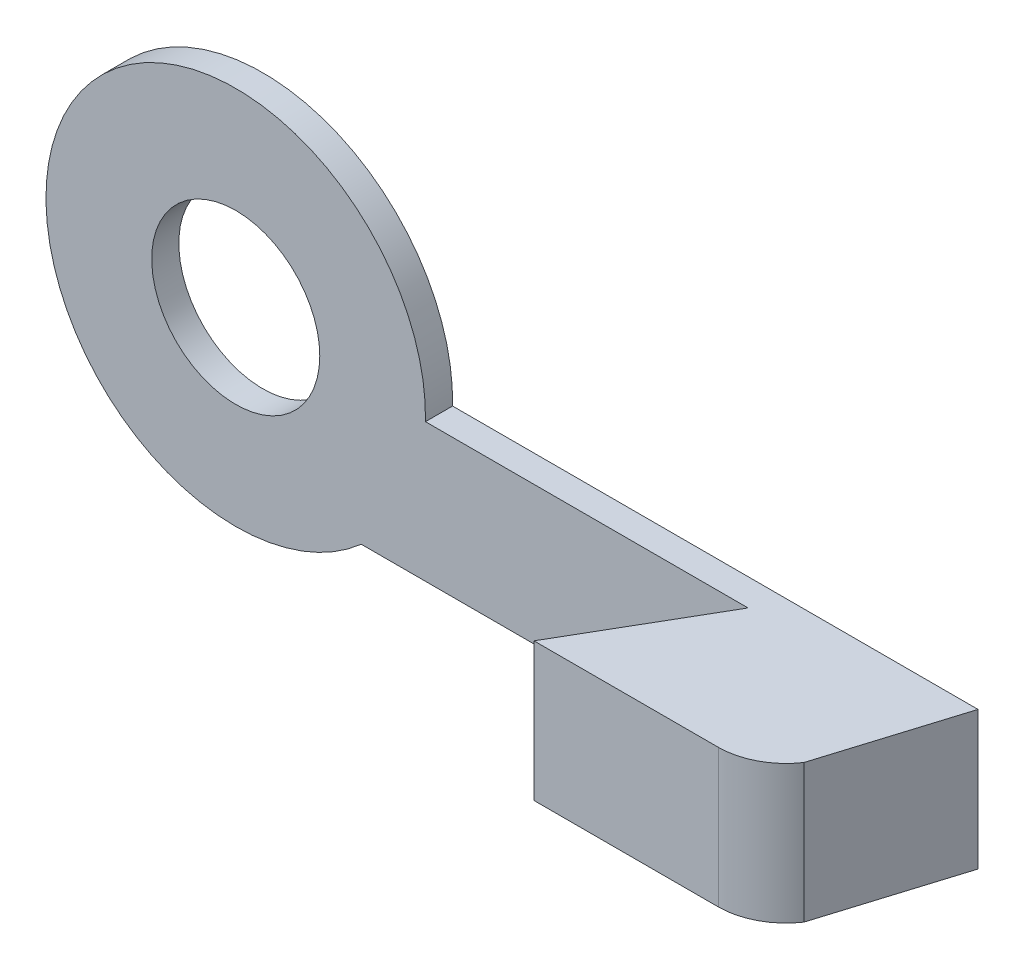
SolidWorks part; units mm, degrees
ref_plane "Front" through (0, 0, 0) normal (0, 0, 1) x (1, 0, 0)
ref_plane "Top" through (0, 0, 0) normal (0, 1, 0) x (1, 0, 0)
ref_plane "Right" through (0, 0, 0) normal (1, 0, 0) x (0, 0, -1)
sketch "Sketch3" plane through (0, 0, 0) normal (0, 1, 0) x (1, 0, 0)
  line L0 (0, -2.5) -> (-3.9, -2.5)
  line L1 (-3.9, -2.5) -> (-3.9, 3.5)
  line L2 (-3.9, 3.5) -> (-1, 3.5)
  arc A0 (2.5, 0) -> (0, -2.5) centre (0, 0) cw
  arc A1 (-1, 3.5) -> (2.5, 0) centre (-1, 0) cw
  dimension "D1" = 2.5
  dimension "D2" = 6.4
  dimension "D3" = 6
extrude "Boss-Extrude1" add sketch "Sketch3" along normal blind 5.1
sketch "Sketch4" plane through (-3.9, 0, 0) normal (-1, 0, 0) x (0, 0, 1)
  line L1 (-3.5, 5.1) -> (-2.5, 5.1)
  line L2 (-3.5, 5.1) -> (-3.5, 0)
  line L3 (-3.5, 0) -> (-2.5, 0)
  line L4 (-2.5, 5.1) -> (-2.5, 0)
  dimension "D1" = 1
extrude "Boss-Extrude2" add sketch "Sketch4" along normal blind 18.9
sketch "Sketch5" plane through (0, 0, -3.5) normal (0, 0, -1) x (-1, 0, 0)
  line L0 (22.8, 5.1) -> (22.8, 0) construction
  line L2 (1, 5.1) -> (22.8, 5.1) construction
  circle A0 centre (22.8, 5.25) radius 7
  dimension "D2" = 14
  dimension "D1" = 0.15
extrude "Boss-Extrude3" add sketch "Sketch5" against normal blind 1
sketch "Sketch6" plane through (0, 0, -2.5) normal (0, 0, 1) x (1, 0, 0)
  circle A0 centre (-22.8, 5.25) radius 3.1
  circle A1 centre (-22.8, 5.25) radius 7 construction
  dimension "D1" = 6.2
extrude "Cut-Extrude1" cut sketch "Sketch6" against normal through all both and the other way through all
sketch "Sketch7" plane through (0, 0, 0) normal (0, -1, 0) x (1, 0, 0)
  line L3 (-3.9, -2.5) -> (-3.9, 2.5)
  line L4 (-3.9, 2.5) -> (-6.8, 2.5)
  line L5 (-6.8, 2.5) -> (-3.9, -2.5)
  dimension "D1" = 2.9
extrude "Boss-Extrude4" add sketch "Sketch7" against normal up to surface (5.1 mm away) up to face at (-5.2372, 5.1, -1.0296)
sketch "Sketch8" plane through (0, 5.1, 0) normal (0, 1, 0) x (1, 0, 0)
  line L0 (2.5, 0) -> (0.957, -5)
  line L1 (0.957, -5) -> (5.957, -5)
  line L2 (5.957, -5) -> (5.957, 0)
  line L3 (5.957, 0) -> (2.5, 0)
  line L4 (-6.8, -2.5) -> (0, -2.5) construction
  dimension "D1" = 72.85
  dimension "D2" = 5
  dimension "D3" = 5
extrude "Cut-Extrude2" cut sketch "Sketch8" against normal blind 10
sketch "Sketch9" plane through (0, 0, 0) normal (0, 1, 0) x (1, 0, 0)
  line L0 (2.5, 0) -> (3.5801, 3.5)
  line L1 (3.5801, 3.5) -> (-1, 3.5)
  line L2 (-1, 3.5) -> (2.5, 0)
  line L3 (2.5, 0) -> (2.0652, -1.4088) construction
  arc A0 (2.5, 0) -> (-1, 3.5) centre (-1, 0) ccw construction
extrude "Boss-Extrude5" add sketch "Sketch9" along normal up to surface (5.1 mm away) up to face at (-4.7347, 5.1, -0.7575)
